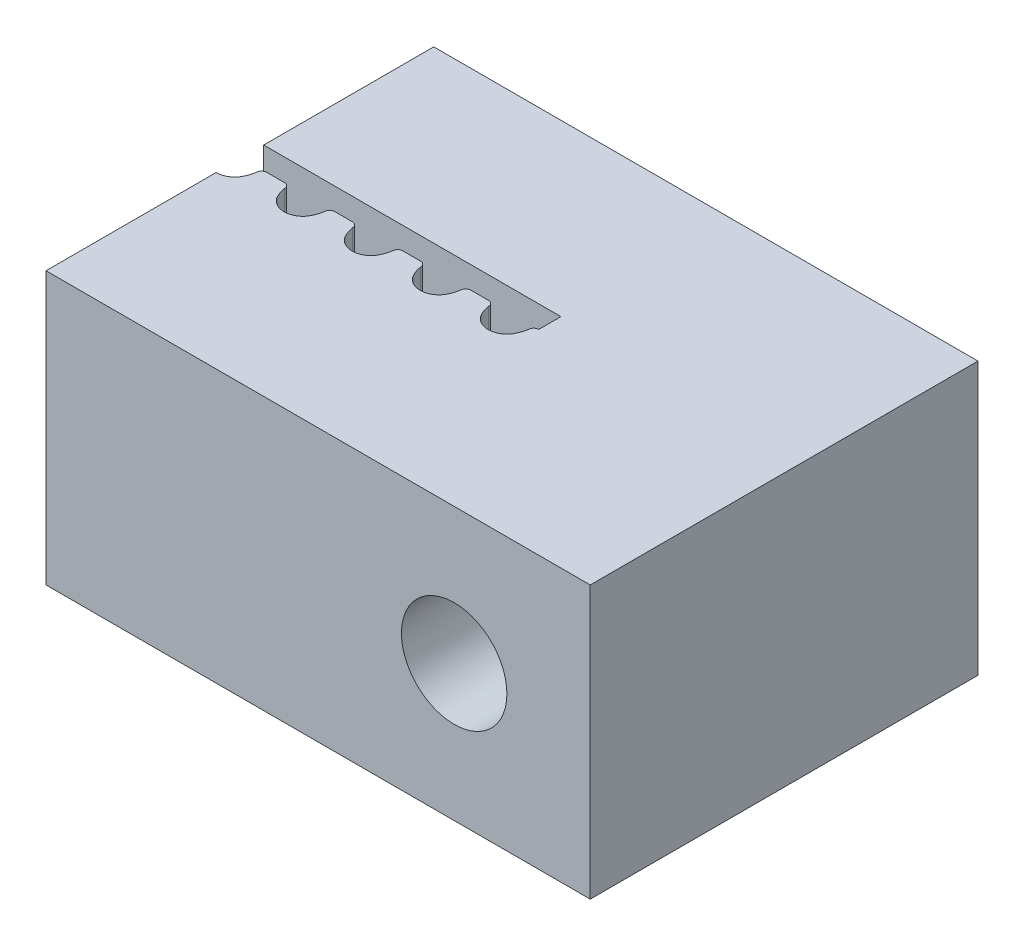
SolidWorks part; units mm, degrees
ref_plane "Front" through (0, 0, 0) normal (0, 0, 1) x (1, 0, 0)
ref_plane "Top" through (0, 0, 0) normal (0, 1, 0) x (1, 0, 0)
ref_plane "Right" through (0, 0, 0) normal (1, 0, 0) x (0, 0, -1)
sketch "Sketch1" plane through (0, 0, 0) normal (0, 1, 0) x (1, 0, 0)
  line L0 (-0.7379, 0.195) -> (-1.2621, 0.195)
  line L1 (-1, 0.195) -> (-1, 0.0683) construction
  line L2 (1.2621, 0.195) -> (0.7379, 0.195)
  line L3 (1, 0.195) -> (1, 0.0683) construction
  line L4 (3.2621, 0.195) -> (2.7379, 0.195)
  line L5 (3, 0.195) -> (3, 0.0683) construction
  line L6 (5.2621, 0.195) -> (4.7379, 0.195)
  line L7 (5, 0.195) -> (5, 0.0683) construction
  line L8 (7.2621, 0.195) -> (6.7379, 0.195)
  line L9 (7, 0.195) -> (7, 0.0683) construction
  line L10 (9.2621, 0.195) -> (8.7379, 0.195)
  line L11 (9, 0.195) -> (9, 0.0683) construction
  line L12 (11.2621, 0.195) -> (10.7379, 0.195)
  line L13 (11, 0.195) -> (11, 0.0683) construction
  line L15 (13.2621, 0.195) -> (12.7379, 0.195)
  line L17 (13, 0.195) -> (13, 0.0683) construction
  line L19 (14, -0.555) -> (14, -5.555)
  line L40 (-2, -0.555) -> (-2, -5.555)
  line L41 (-2, -5.555) -> (14, -5.555)
  arc A0 (-0.4589, -0.3122) -> (0, -0.555) centre (0, 0) ccw
  arc A1 (-0.4589, -0.3122) -> (-0.5879, 0.045) centre (0.4, 0.2) cw
  arc A2 (-0.5879, 0.045) -> (-0.7379, 0.195) centre (-0.7379, 0.045) ccw
  arc A3 (-1.4121, 0.045) -> (-1.2621, 0.195) centre (-1.2621, 0.045) cw
  arc A4 (-1.5411, -0.3122) -> (-1.4121, 0.045) centre (-2.4, 0.2) ccw
  arc A5 (-1.5411, -0.3122) -> (-2, -0.555) centre (-2, 0) cw
  arc A6 (1.5411, -0.3122) -> (2, -0.555) centre (2, 0) ccw
  arc A7 (1.5411, -0.3122) -> (1.4121, 0.045) centre (2.4, 0.2) cw
  arc A8 (1.4121, 0.045) -> (1.2621, 0.195) centre (1.2621, 0.045) ccw
  arc A9 (0.5879, 0.045) -> (0.7379, 0.195) centre (0.7379, 0.045) cw
  arc A10 (0.4589, -0.3122) -> (0.5879, 0.045) centre (-0.4, 0.2) ccw
  arc A11 (0.4589, -0.3122) -> (0, -0.555) centre (0, 0) cw
  arc A12 (3.5411, -0.3122) -> (4, -0.555) centre (4, 0) ccw
  arc A13 (3.5411, -0.3122) -> (3.4121, 0.045) centre (4.4, 0.2) cw
  arc A14 (3.4121, 0.045) -> (3.2621, 0.195) centre (3.2621, 0.045) ccw
  arc A15 (2.5879, 0.045) -> (2.7379, 0.195) centre (2.7379, 0.045) cw
  arc A16 (2.4589, -0.3122) -> (2.5879, 0.045) centre (1.6, 0.2) ccw
  arc A17 (2.4589, -0.3122) -> (2, -0.555) centre (2, 0) cw
  arc A18 (5.5411, -0.3122) -> (6, -0.555) centre (6, 0) ccw
  arc A19 (5.5411, -0.3122) -> (5.4121, 0.045) centre (6.4, 0.2) cw
  arc A20 (5.4121, 0.045) -> (5.2621, 0.195) centre (5.2621, 0.045) ccw
  arc A21 (4.5879, 0.045) -> (4.7379, 0.195) centre (4.7379, 0.045) cw
  arc A22 (4.4589, -0.3122) -> (4.5879, 0.045) centre (3.6, 0.2) ccw
  arc A23 (4.4589, -0.3122) -> (4, -0.555) centre (4, 0) cw
  arc A24 (7.5411, -0.3122) -> (8, -0.555) centre (8, 0) ccw
  arc A25 (7.5411, -0.3122) -> (7.4121, 0.045) centre (8.4, 0.2) cw
  arc A26 (7.4121, 0.045) -> (7.2621, 0.195) centre (7.2621, 0.045) ccw
  arc A27 (6.5879, 0.045) -> (6.7379, 0.195) centre (6.7379, 0.045) cw
  arc A28 (6.4589, -0.3122) -> (6.5879, 0.045) centre (5.6, 0.2) ccw
  arc A29 (6.4589, -0.3122) -> (6, -0.555) centre (6, 0) cw
  arc A30 (9.5411, -0.3122) -> (10, -0.555) centre (10, 0) ccw
  arc A31 (9.5411, -0.3122) -> (9.4121, 0.045) centre (10.4, 0.2) cw
  arc A32 (9.4121, 0.045) -> (9.2621, 0.195) centre (9.2621, 0.045) ccw
  arc A33 (8.5879, 0.045) -> (8.7379, 0.195) centre (8.7379, 0.045) cw
  arc A34 (8.4589, -0.3122) -> (8.5879, 0.045) centre (7.6, 0.2) ccw
  arc A35 (8.4589, -0.3122) -> (8, -0.555) centre (8, 0) cw
  arc A36 (11.5411, -0.3122) -> (12, -0.555) centre (12, 0) ccw
  arc A37 (11.5411, -0.3122) -> (11.4121, 0.045) centre (12.4, 0.2) cw
  arc A38 (11.4121, 0.045) -> (11.2621, 0.195) centre (11.2621, 0.045) ccw
  arc A39 (10.5879, 0.045) -> (10.7379, 0.195) centre (10.7379, 0.045) cw
  arc A40 (10.4589, -0.3122) -> (10.5879, 0.045) centre (9.6, 0.2) ccw
  arc A41 (10.4589, -0.3122) -> (10, -0.555) centre (10, 0) cw
  arc A48 (13.5411, -0.3122) -> (14, -0.555) centre (14, 0) ccw
  arc A49 (13.5411, -0.3122) -> (13.4121, 0.045) centre (14.4, 0.2) cw
  arc A50 (13.4121, 0.045) -> (13.2621, 0.195) centre (13.2621, 0.045) ccw
  arc A51 (12.5879, 0.045) -> (12.7379, 0.195) centre (12.7379, 0.045) cw
  arc A52 (12.4589, -0.3122) -> (12.5879, 0.045) centre (11.6, 0.2) ccw
  arc A53 (12.4589, -0.3122) -> (12, -0.555) centre (12, 0) cw
  dimension "D1" = 0.555
  dimension "D2" = 0.4
  dimension "D4" = 0.15
  dimension "D6" = 1
  dimension "D3" = 0.2
  dimension "D5" = 0.75
  dimension "D7" = 2
  dimension "D9" = 5
  dimension "D8" = 8
extrude "Boss-Extrude1" add sketch "Sketch1" along normal blind 8
sketch "Sketch3" plane through (0, 8, 0) normal (0, 1, 0) x (1, 0, 0)
  line L0 (7, 0.195) -> (14, 0.195)
  line L1 (14, -0.555) -> (14, 0.195)
  line L2 (14, -0.555) -> (7, -0.555)
  line L3 (7, -0.555) -> (7, 0.195)
  line L6 (7.2621, 0.195) -> (6.7379, 0.195) construction
extrude "Boss-Extrude2" add sketch "Sketch3" against normal blind 8
sketch "Sketch4" plane through (0, 8, 0) normal (0, 1, 0) x (1, 0, 0)
  line L0 (6.7379, 0.195) -> (6.7379, 0.845)
  line L1 (6.7379, 0.845) -> (-2, 0.845)
  line L2 (-2, 0.845) -> (-2, 5.845)
  line L3 (-2, 5.845) -> (14, 5.845)
  line L4 (14, 5.845) -> (14, 0.195)
  line L5 (14, 0.195) -> (6.7379, 0.195) construction
  line L6 (-2, -0.555) -> (-2, -5.555) construction
  line L7 (-2, -0.555) -> (-2, 0.845) construction
  line L8 (6.7379, 0.195) -> (14, 0.195)
  dimension "D1" = 5
  dimension "D2" = 1.4
extrude "Boss-Extrude3" add sketch "Sketch4" against normal up to surface (8 mm away) up to face at (2.9613, 0, 0.4169)
sketch "Sketch2" plane through (0, 0, 5.555) normal (0, 0, 1) x (1, 0, 0)
  line L0 (14, 4) -> (10, 4) construction
  line L2 (14, 8) -> (14, 0) construction
  circle A0 centre (10, 4) radius 1.55
  dimension "D2" = 3.1
  dimension "D1" = 4
extrude "Cut-Extrude1" cut sketch "Sketch2" against normal up to next contours A0
